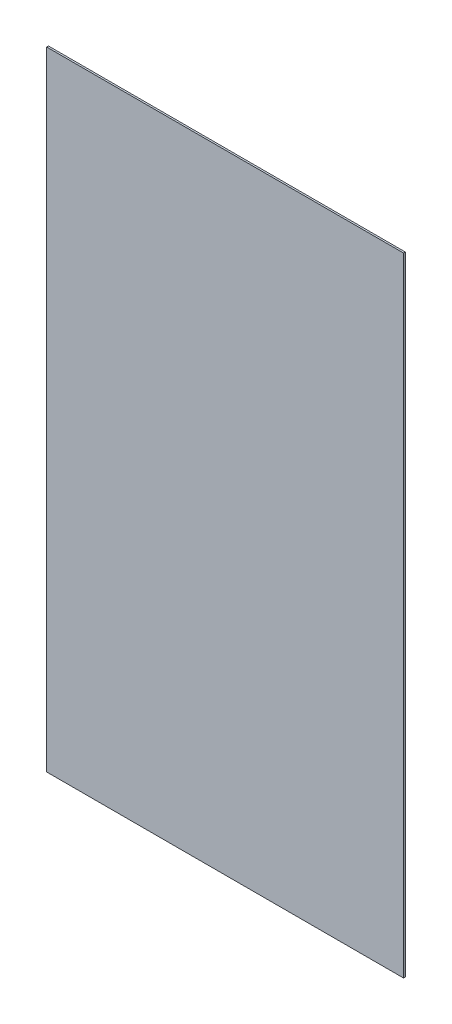
SolidWorks part; units mm, degrees
ref_plane "Front Plane" through (0, 0, 0) normal (0, 0, 1) x (1, 0, 0)
ref_plane "Top Plane" through (0, 0, 0) normal (0, 1, 0) x (1, 0, 0)
ref_plane "Right Plane" through (0, 0, 0) normal (1, 0, 0) x (0, 0, -1)
ref_plane "Plane1" through (0, 0, 0.25) normal (0, 0, 1) x (1, 0, 0)
sketch "Sketch1" plane through (0, 0, 0.25) normal (0, 0, 1) x (1, 0, 0)
  line L0 (25, -46.4821) -> (25, 41.5179)
  line L1 (25, 41.5179) -> (-25, 41.5179)
  line L2 (-25, 41.5179) -> (-25, -46.4821)
  line L3 (-25, -46.4821) -> (25, -46.4821)
  dimension "D1" = 50
  dimension "D2" = 88
  dimension "D3" = 25
  dimension "D4" = 41.5179
extrude "Boss-Extrude1" add sketch "Sketch1" against normal blind 0.25
